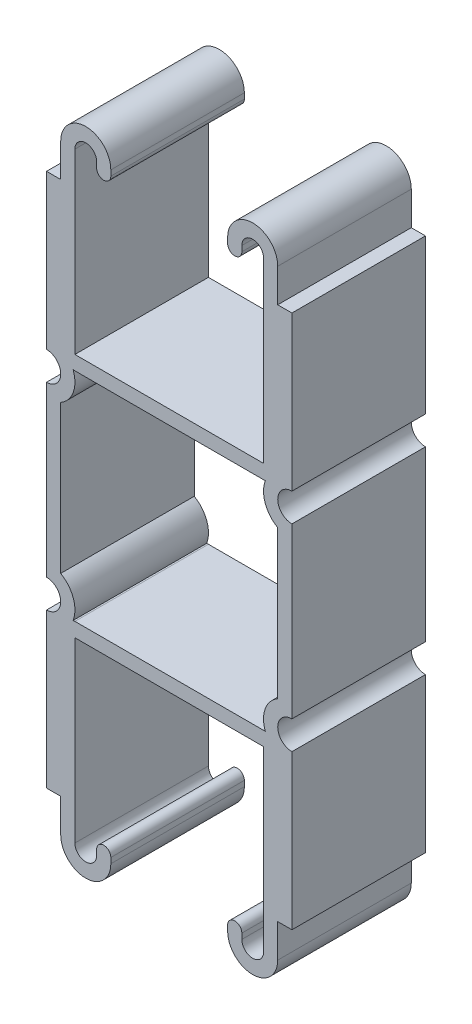
SolidWorks part; units mm, degrees
ref_plane "Plane1" through (0, 0, 0) normal (0, 0, 1) x (1, 0, 0)
ref_plane "Plane2" through (0, 0, 0) normal (0, 1, 0) x (1, 0, 0)
ref_plane "Plane3" through (0, 0, 0) normal (1, 0, 0) x (0, 0, -1)
sketch "Sketch1" plane through (0, 33.02, 0) normal (0, 0, 1) x (1, 0, 0)
  line L0 (-20.6375, 24.13) -> (-20.6375, -9.6901)
  line L1 (-17.9451, -12.3825) -> (17.9451, -12.3825)
  line L2 (20.6375, -9.6901) -> (20.6375, 24.13)
  line L3 (11.1125, 24.13) -> (11.1125, 23.095)
  line L4 (-11.1125, 24.13) -> (-11.1125, 23.095)
  line L5 (-13.8049, 24.13) -> (-13.8049, 23.095)
  line L6 (-17.9451, 24.13) -> (-17.9451, -9.6901)
  line L7 (-17.9451, -9.6901) -> (17.9451, -9.6901)
  line L8 (17.9451, -9.6901) -> (17.9451, 24.13)
  line L9 (13.8049, 24.13) -> (13.8049, 23.095)
  line L10 (-25.4, 28.8925) -> (25.4, 28.8925) construction
  line L11 (-12.8524, 21.7488) -> (12.8524, 21.7488) construction
  arc A0 (20.6375, 24.13) -> (11.1125, 24.13) centre (15.875, 24.13) ccw
  arc A1 (-20.6375, 24.13) -> (-11.1125, 24.13) centre (-15.875, 24.13) cw
  arc A2 (-17.9451, -12.3825) -> (-20.6375, -9.6901) centre (-17.9451, -9.6901) cw
  arc A3 (17.9451, -12.3825) -> (20.6375, -9.6901) centre (17.9451, -9.6901) ccw
  arc A4 (-17.9451, 24.13) -> (-13.8049, 24.13) centre (-15.875, 24.13) cw
  arc A5 (17.9451, 24.13) -> (13.8049, 24.13) centre (15.875, 24.13) ccw
  arc A6 (11.1125, 23.095) -> (13.8049, 23.095) centre (12.4587, 23.095) ccw
  arc A7 (-11.1125, 23.095) -> (-13.8049, 23.095) centre (-12.4587, 23.095) cw
  dimension "D1" = 2.6924
  dimension "Width" = 41.275
  dimension "D6" = 9.525
  dimension "D7" = 22.225
  dimension "D9" = 7.1437
  dimension "D2" = 41.275
  dimension "D3" = 20.6375
  dimension "D4" = 20.6375
  dimension "gauge" = 2.6924
extrude "Base-Extrude" add sketch "Sketch1" along normal mid plane 25.4
sketch "Sketch2" plane through (0, 0, 0) normal (0, 0, 1) x (1, 0, 0)
  line L0 (-23.3375, 50.8) -> (-23.3375, 21.4579)
  line L1 (-23.3375, 16.0579) -> (-23.3375, -16.0579)
  line L2 (-20.6375, 50.8) -> (-20.6375, 23.4344)
  line L3 (-20.6375, 14.0814) -> (-20.6375, -14.0814)
  line L5 (-23.3375, -21.4579) -> (-23.3375, -50.8)
  line L6 (-20.6375, -23.4344) -> (-20.6375, -50.8)
  line L7 (-23.3375, 50.8) -> (-20.6375, 50.8)
  line L8 (-23.3375, -50.8) -> (-20.6375, -50.8)
  arc A0 (-23.3375, 16.0579) -> (-23.3375, 21.4579) centre (-23.3375, 18.7579) ccw
  arc A1 (-20.6375, 14.0814) -> (-20.6375, 23.4344) centre (-23.3375, 18.7579) ccw
  arc A2 (-20.6375, -14.0814) -> (-20.6375, -23.4344) centre (-23.3375, -18.7579) cw
  arc A3 (-23.3375, -16.0579) -> (-23.3375, -21.4579) centre (-23.3375, -18.7579) cw
  dimension "D4" = 18.7579
  dimension "D3" = 2.7
  dimension "D9" = 5.4
  dimension "D1" = 20.6375
  dimension "D2" = 50.8
  dimension "gauge" = 2.7
  dimension "D6" = 101.6
  dimension "D11" = 37.5158
extrude "Boss-Extrude1" add sketch "Sketch2" along normal mid plane 25.4
mirror "Mirror1" about plane through (0, 0, 0) normal (0, 1, 0) of "Base-Extrude"
mirror "Mirror2" about plane through (0, 0, 0) normal (1, 0, 0) of "Boss-Extrude1"
equation "\"D3@Sketch1\" = \"Width@Sketch1\" / 2"
equation "\"D7@Sketch1\" = \"Width@Sketch1\" - 2 * \"D6@Sketch1\""
equation "\"D1@Sketch1\" = \"gauge@Sketch1\""
equation "\"D1@Boss-Extrude1\" = \"D1@Base-Extrude\""
